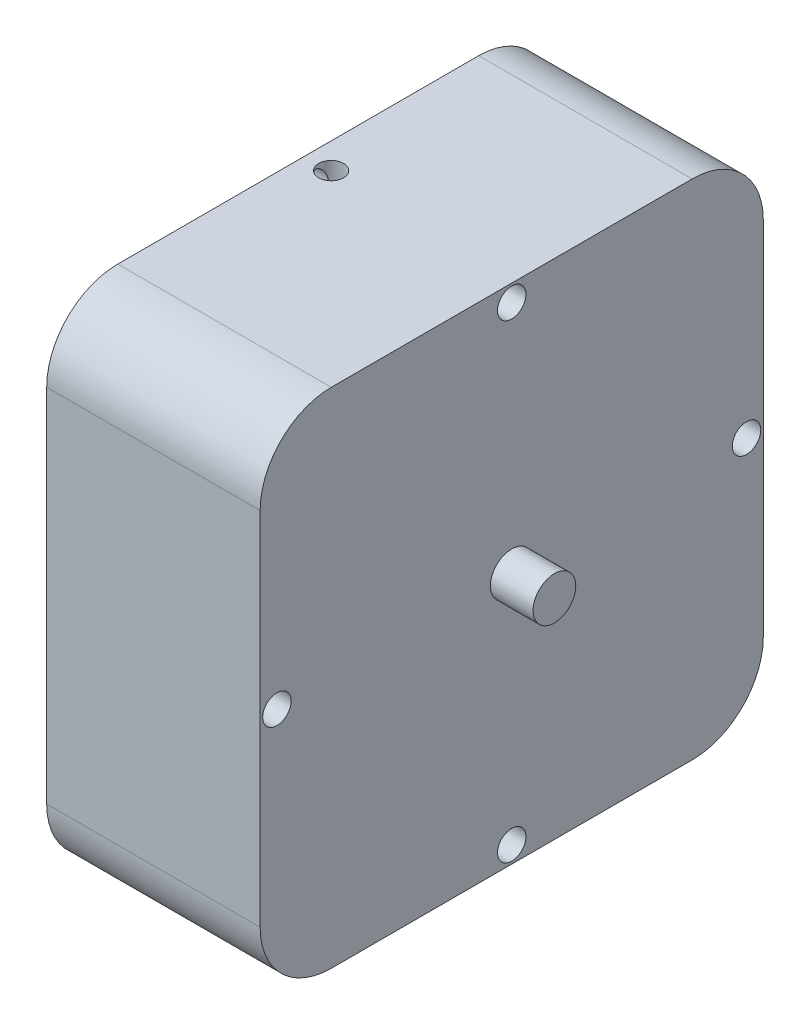
SolidWorks part; units mm, degrees
ref_plane "前视基准面" through (0, 0, 0) normal (0, 0, 1) x (1, 0, 0)
ref_plane "上视基准面" through (0, 0, 0) normal (0, 1, 0) x (1, 0, 0)
ref_plane "右视基准面" through (0, 0, 0) normal (1, 0, 0) x (0, 0, -1)
sketch "草图1" plane through (0, 0, 0) normal (1, 0, 0) x (0, 0, -1)
  line L1 (-35.36, 35.36) -> (35.36, 35.36)
  line L2 (-35.36, 35.36) -> (-35.36, -35.36)
  line L3 (-35.36, -35.36) -> (35.36, -35.36)
  line L4 (35.36, 35.36) -> (35.36, -35.36)
  line L5 (-35.36, 35.36) -> (35.36, -35.36) construction
  line L6 (-35.36, -35.36) -> (35.36, 35.36) construction
  point P0 (0, 0)
  dimension "D1" = 70.72
  dimension "D2" = 70.72
extrude "凸台-拉伸1" add sketch "草图1" along normal blind 30
sketch "草图2" plane through (0, 0, 0) normal (-1, 0, 0) x (0, 0, 1)
  circle A0 centre (0, 0) radius 3
  dimension "D1" = 6
extrude "切除-拉伸1" cut sketch "草图2" against normal blind 6
sketch "草图3" plane through (30, 0, 0) normal (1, 0, 0) x (0, 0, -1)
  circle A0 centre (0, 0) radius 3
extrude "凸台-拉伸2" add sketch "草图3" along normal blind 6
cosmetic thread "装饰螺纹线1" parameters "D2"=4.917
cosmetic thread "装饰螺纹线2" parameters "D2"=4.917
sketch "草图5" plane through (0, 35.36, 0) normal (0, 1, 0) x (1, 0, 0)
  line L0 (30, 0) -> (30, 1)
  line L1 (30, 35.36) -> (30, -35.36) construction
  circle A0 centre (3.62, 1) radius 1.75
extrude "切除-拉伸2" cut sketch "草图5" against normal blind 6 contours A0
sketch "草图7" plane through (6, 0, 0) normal (-1, 0, 0) x (0, 0, 1)
  line L0 (0, 0) -> (0, -33) construction
  line L1 (0, 0) -> (0, 33) construction
  circle A0 centre (0, 0) radius 33 construction
  circle A1 centre (0, 33) radius 2
  circle A2 centre (33, 0) radius 2
  circle A3 centre (0, -33) radius 2
  circle A4 centre (-33, 0) radius 2
  point P15 (0, 0)
  dimension "D1" = 4
extrude "切除-拉伸3" cut sketch "草图7" against normal through all both and the other way through all
fillet "圆角1" radius 10 1 edges at (15, 35.36, -35.36)
fillet "圆角2" radius 10 1 edges at (15, -35.36, -35.36)
fillet "圆角3" radius 10 1 edges at (15, -35.36, 35.36)
fillet "圆角4" radius 10 1 edges at (15, 35.36, 35.36)
